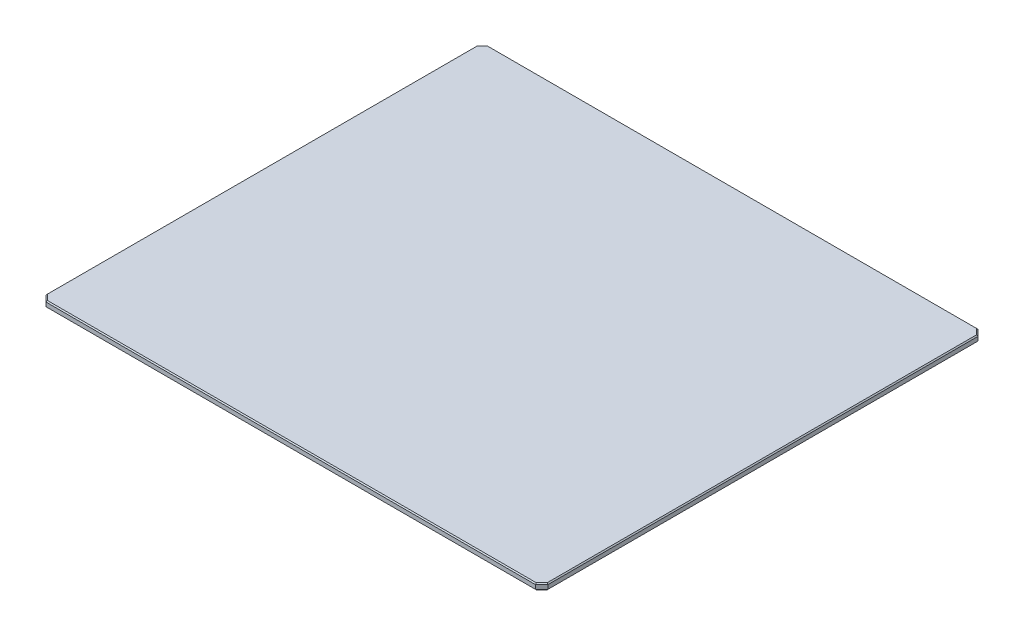
SolidWorks part; units mm, degrees
ref_plane "Alzado" through (0, 0, 0) normal (0, 0, 1) x (1, 0, 0)
ref_plane "Planta" through (0, 0, 0) normal (0, 1, 0) x (1, 0, 0)
ref_plane "Vista lateral" through (0, 0, 0) normal (1, 0, 0) x (0, 0, -1)
sketch "Croquis1" plane through (0, 78.9788, 0) normal (0, 1, 0) x (1, 0, 0)
  line L0 (-151.5288, -66.7897) -> (-151.5288, -282.7744) construction
  line L1 (-151.5288, -282.7744) -> (93.4712, -282.7744) construction
  line L2 (93.4712, -282.7744) -> (93.4712, -66.7897) construction
  line L3 (93.4712, -66.7897) -> (-151.5288, -66.7897) construction
  line L4 (-151.5288, -66.7897) -> (-151.5288, -282.7744)
  line L5 (-151.5288, -282.7744) -> (93.4712, -282.7744)
  line L6 (93.4712, -282.7744) -> (93.4712, -66.7897)
  line L7 (93.4712, -66.7897) -> (-151.5288, -66.7897)
extrude "Saliente-Extruir1" add sketch "Croquis1" along normal blind 3
chamfer "Chaflán1" distance 3 angle 45 4 edges at (-151.5288, 80.4788, 66.7897) (-151.5288, 80.4788, 282.7744) (93.4712, 80.4788, 66.7897) (93.4712, 80.4788, 282.7744)
chamfer "Chaflán2" distance 0.5 angle 45 8 edges at (91.9712, 81.9788, 68.2897) (93.4712, 81.9788, 174.7821) (91.9712, 81.9788, 281.2744) (-29.0288, 81.9788, 282.7744) (-150.0288, 81.9788, 281.2744) (-151.5288, 81.9788, 174.7821) (-150.0288, 81.9788, 68.2897) (-29.0288, 81.9788, 66.7897)
chamfer "Chaflán3" distance 0.5 angle 45 8 edges at (-150.0288, 78.9788, 281.2744) (-29.0288, 78.9788, 282.7744) (91.9712, 78.9788, 281.2744) (93.4712, 78.9788, 174.7821) (91.9712, 78.9788, 68.2897) (-29.0288, 78.9788, 66.7897) (-150.0288, 78.9788, 68.2897) (-151.5288, 78.9788, 174.7821)
